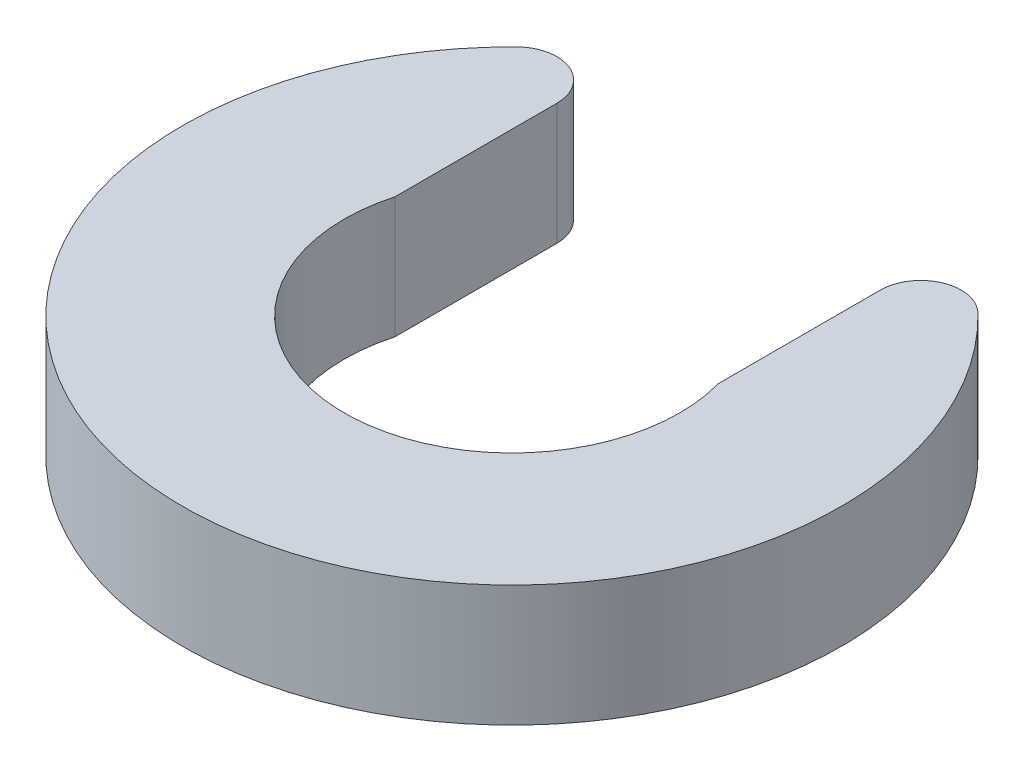
SolidWorks part; units mm, degrees
ref_plane "Front Plane" through (0, 0, 0) normal (0, 0, 1) x (1, 0, 0)
ref_plane "Top Plane" through (0, 0, 0) normal (0, 1, 0) x (1, 0, 0)
ref_plane "Right Plane" through (0, 0, 0) normal (1, 0, 0) x (0, 0, -1)
sketch "Sketch1" plane through (0, 0, 0) normal (0, 1, 0) x (1, 0, 0)
  line L0 (0, 0) -> (0, 8.15) construction
  line L2 (4, 8.075) -> (-4, 8.075)
  line L3 (4, 8.075) -> (4, 0.075)
  line L4 (4, 0.075) -> (-4, 0.075)
  line L5 (-4, 8.075) -> (-4, 0.075)
  line L6 (4, 8.075) -> (-4, 0.075) construction
  line L7 (4, 0.075) -> (-4, 8.075) construction
  circle A0 centre (0, 0) radius 4.15
  circle A1 centre (0, 0) radius 8.15
  point P4 (0, 4.075)
  dimension "D1" = 8.3
  dimension "D2" = 4
  dimension "D3" = 8
  dimension "D4" = 8
extrude "Boss-Extrude1" add sketch "Sketch1" along normal blind 3 contours L5 A1 L3 A0
fillet "Fillet1" radius 1 2 edges at (4, 1.5, -7.1009) (-4, 1.5, -7.1009)
